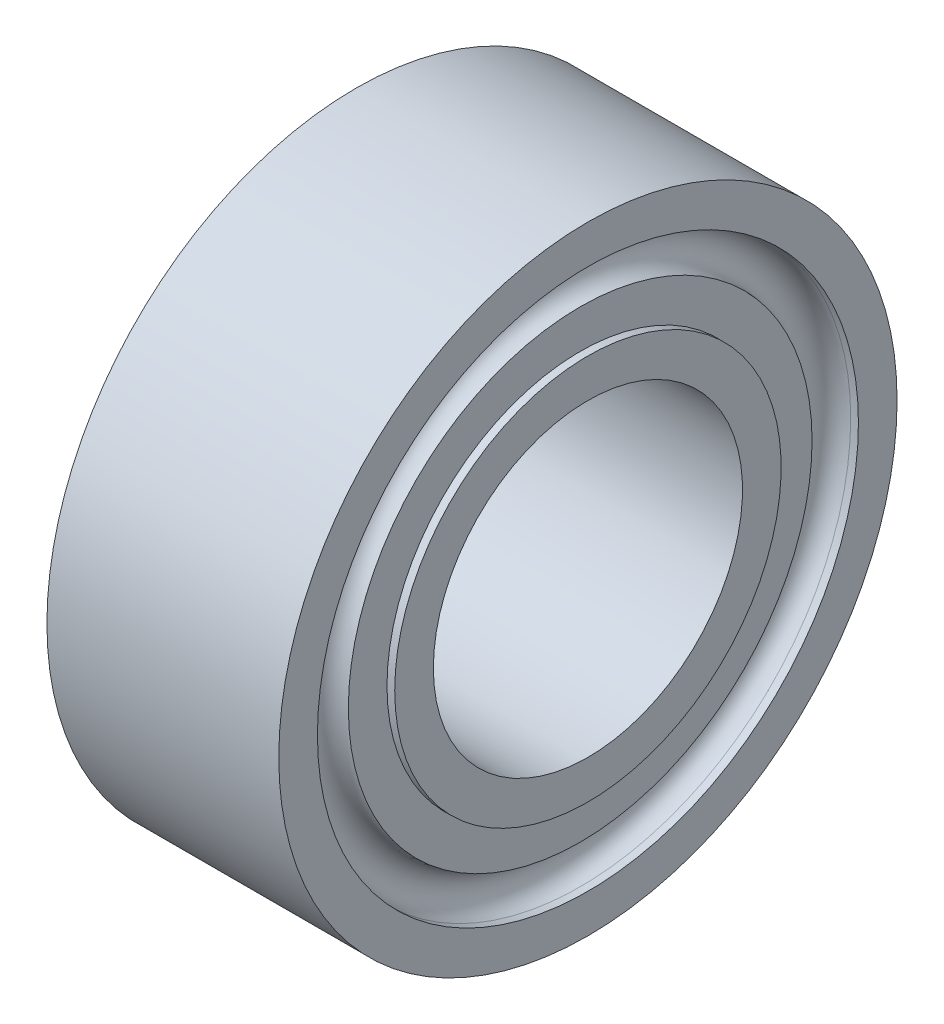
SolidWorks part; units mm, degrees
ref_plane "前视基准面" through (0, 0, 0) normal (0, 0, 1) x (1, 0, 0)
ref_plane "上视基准面" through (0, 0, 0) normal (0, 1, 0) x (1, 0, 0)
ref_plane "右视基准面" through (0, 0, 0) normal (1, 0, 0) x (0, 0, -1)
sketch "草图1" plane through (0, 0, 0) normal (0, 0, 1) x (1, 0, 0)
  line L0 (0, 0) -> (3, 0) construction
  line L1 (0, 0) -> (0, 2) construction
  line L2 (0, 2) -> (3, 2)
  line L3 (3, 2) -> (3, 2.5)
  line L4 (3, 4) -> (0, 4)
  line L6 (3, 2) -> (3, 2.5)
  line L7 (3, 2.5) -> (2.9, 2.5)
  line L8 (2.9, 2.5) -> (2.9, 3)
  line L11 (2.9, 3.5) -> (3, 3.5)
  line L12 (3, 3.5) -> (3, 4)
  line L13 (1.5, 4) -> (1.5, 3.3466) construction
  line L14 (0, 2) -> (0, 2.5)
  line L15 (0, 2.5) -> (0.1, 2.5)
  line L16 (0.1, 2.5) -> (0.1, 3)
  line L17 (0.1, 3.5) -> (0, 3.5)
  line L18 (0, 3.5) -> (0, 4)
  arc A0 (2.9, 3.5) -> (2.9, 3) centre (2.9, 3.25) ccw
  arc A1 (0.1, 3.5) -> (0.1, 3) centre (0.1, 3.25) cw
  point P13 (0, 0)
  point P16 (0, 0)
  dimension "D6" = 0.25
  dimension "D1" = 1.5
  dimension "D2" = 2
  dimension "D3" = 2
  dimension "D4" = 0.5
  dimension "D5" = 0.5
  dimension "D7" = 0.5
  dimension "D8" = 0.1
revolve "旋转1" add sketch "草图1" angle 360 about L0
